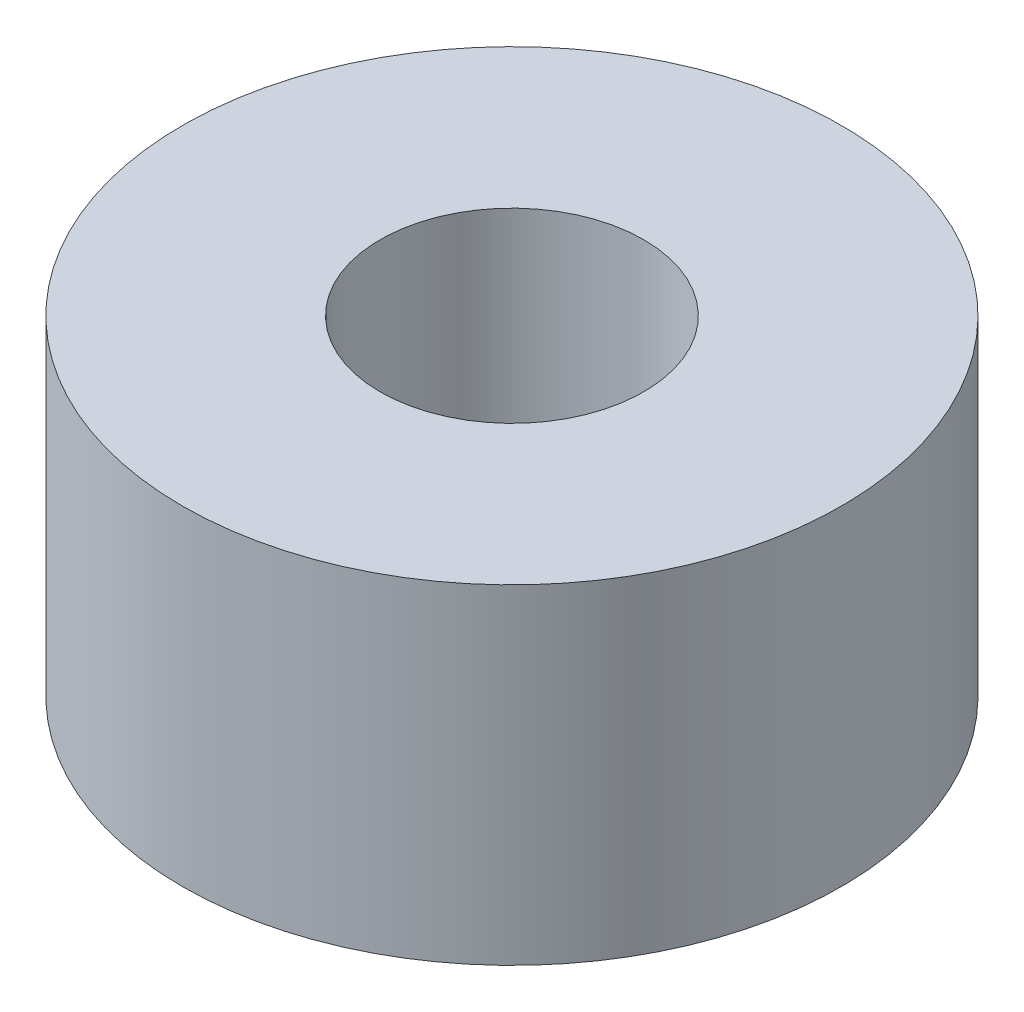
SolidWorks part; units mm, degrees
ref_plane "Front Plane" through (0, 0, 0) normal (0, 0, 1) x (1, 0, 0)
ref_plane "Top Plane" through (0, 0, 0) normal (0, 1, 0) x (1, 0, 0)
ref_plane "Right Plane" through (0, 0, 0) normal (1, 0, 0) x (0, 0, -1)
sketch "Sketch1" plane through (0, 0, 0) normal (0, 1, 0) x (1, 0, 0)
  circle A0 centre (0, 0) radius 2.5
  circle A1 centre (0, 0) radius 1
  dimension "D1" = 5
  dimension "D2" = 2
extrude "Boss-Extrude1" add sketch "Sketch1" along normal blind 2.5
